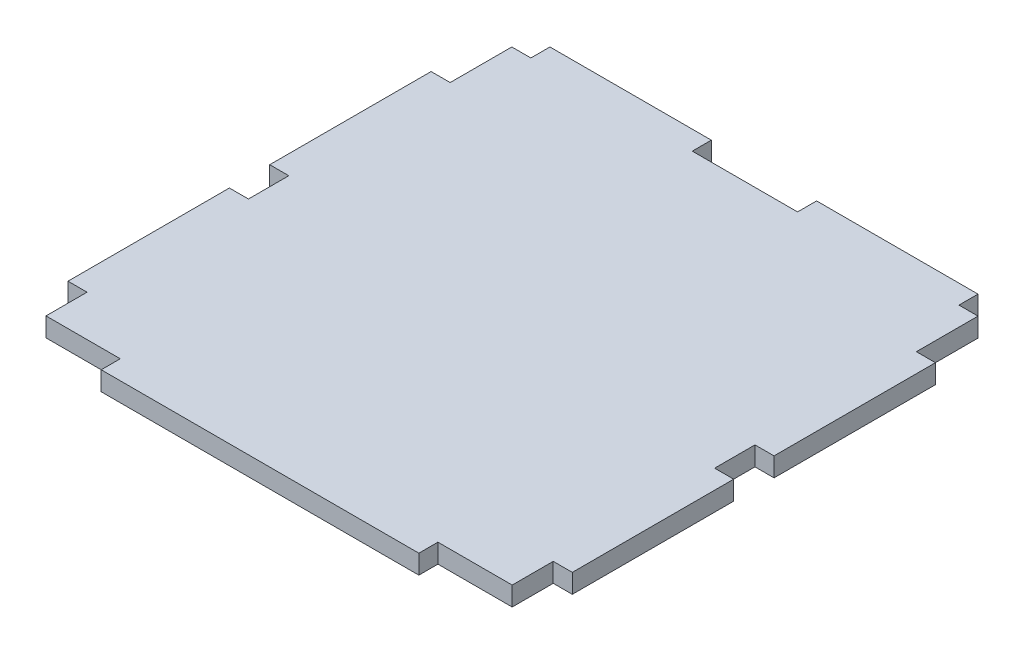
SolidWorks part; units mm, degrees
ref_plane "Front Plane" through (0, 0, 0) normal (0, 0, 1) x (1, 0, 0)
ref_plane "Top Plane" through (0, 0, 0) normal (0, 1, 0) x (1, 0, 0)
ref_plane "Right Plane" through (0, 0, 0) normal (1, 0, 0) x (0, 0, -1)
sketch "Sketch1" plane through (0, 0, 0) normal (0, 1, 0) x (1, 0, 0)
  line L0 (0, 38.155) -> (0, -38.155) construction
  line L1 (36.685, -38.155) -> (-36.685, -38.155)
  line L2 (36.685, -38.155) -> (36.685, -28.695)
  line L3 (-36.685, 38.155) -> (-33.685, 38.155)
  line L4 (-36.685, -38.155) -> (-36.685, -28.695)
  line L5 (36.685, -38.155) -> (-36.685, 38.155) construction
  line L6 (36.685, 38.155) -> (-36.685, -38.155) construction
  line L7 (-39.685, -3.295) -> (-36.685, -3.295)
  line L8 (-36.685, 3.055) -> (-39.685, 3.055)
  line L9 (-39.685, 3.055) -> (-39.685, 28.455)
  line L10 (-39.685, 28.455) -> (-36.685, 28.455)
  line L11 (-36.685, -28.695) -> (-39.685, -28.695)
  line L12 (-39.685, -28.695) -> (-39.685, -3.295)
  line L13 (39.685, 28.455) -> (36.685, 28.455)
  line L14 (36.685, -28.695) -> (39.685, -28.695)
  line L15 (39.685, -28.695) -> (39.685, -3.295)
  line L16 (39.685, -3.295) -> (36.685, -3.295)
  line L17 (36.685, 3.055) -> (39.685, 3.055)
  line L18 (39.685, 3.055) -> (39.685, 28.455)
  line L19 (-36.685, 28.455) -> (-36.685, 38.155)
  line L20 (-36.685, -3.295) -> (-36.685, 3.055)
  line L21 (36.685, 28.455) -> (36.685, 38.155)
  line L22 (36.685, -3.295) -> (36.685, 3.055)
  line L23 (-8.285, 38.155) -> (-8.285, 41.155)
  line L24 (-8.285, 41.155) -> (-33.685, 41.155)
  line L25 (-33.685, 38.155) -> (-33.685, 41.155)
  line L26 (8.285, 38.155) -> (8.285, 41.155)
  line L27 (36.685, 38.155) -> (33.685, 38.155)
  line L28 (33.685, 38.155) -> (33.685, 41.155)
  line L29 (8.285, 38.155) -> (-8.285, 38.155)
  line L30 (33.685, 41.155) -> (8.285, 41.155)
  line L31 (-36.685, -35.155) -> (-24.995, -35.155)
  line L32 (-24.995, -35.155) -> (-24.995, -38.155)
  line L33 (24.995, -35.155) -> (24.995, -38.155)
  line L34 (36.685, -35.155) -> (24.995, -35.155)
  point P0 (0, 0)
  dimension "D1" = 73.37
  dimension "D2" = 3
  dimension "D3" = 3
  dimension "D4" = 3
  dimension "D5" = 6.35
  dimension "D6" = 25.4
  dimension "D7" = 3
  dimension "D8" = 25.4
  dimension "D9" = 25.4
  dimension "D10" = 3
  dimension "D11" = 25.4
  dimension "D12" = 3
  dimension "D13" = 11.69
  dimension "D14" = 3
extrude "Boss-Extrude1" add sketch "Sketch1" along normal blind 3 contours L34 L2 L14 L15 L16 L22 L17 L18 L13 L21 L27 L28 L30 L26 L29 L23 L24 L25 L3 L19 L10 L9 L8 L20 L7 L12 L11 L4 L31 L32 L1 L33
